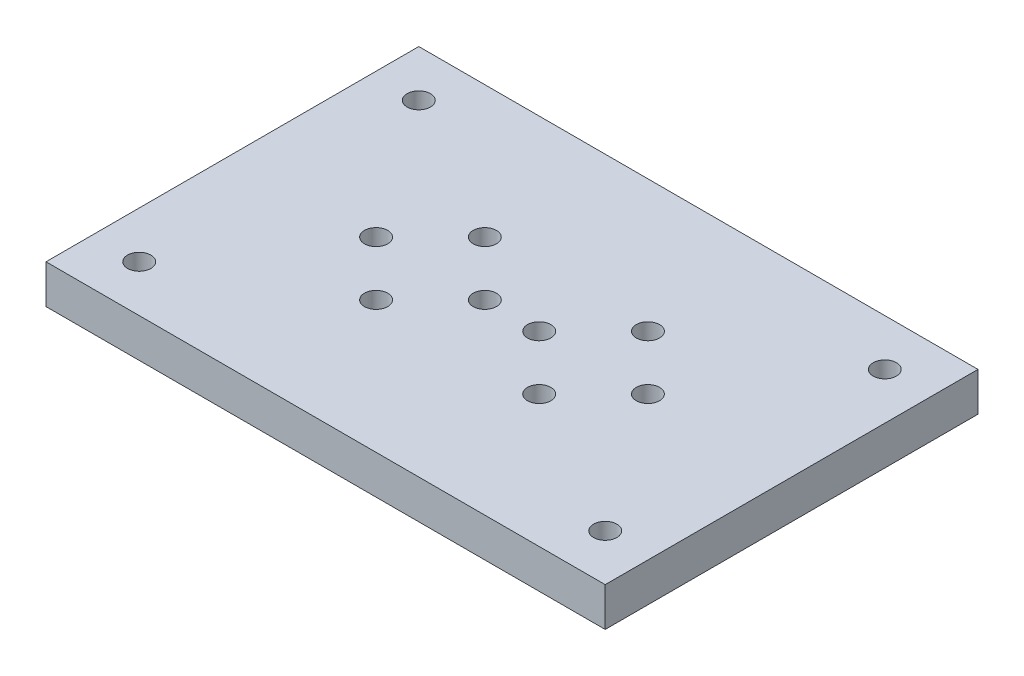
SolidWorks part; units mm, degrees
ref_plane "Front Plane" through (0, 0, 0) normal (0, 0, 1) x (1, 0, 0)
ref_plane "Top Plane" through (0, 0, 0) normal (0, 1, 0) x (1, 0, 0)
ref_plane "Right Plane" through (0, 0, 0) normal (1, 0, 0) x (0, 0, -1)
sketch "Sketch1" plane through (0, 0, 0) normal (0, 1, 0) x (1, 0, 0)
  line L0 (-36, 0) -> (36, 0) construction
  line L1 (-36, -24) -> (36, -24)
  line L2 (-36, -24) -> (-36, 24)
  line L3 (-36, 24) -> (36, 24)
  line L4 (36, -24) -> (36, 24)
  line L5 (-36, -24) -> (36, 24) construction
  line L6 (-36, 24) -> (36, -24) construction
  line L7 (0, -24) -> (0, 24) construction
  line L8 (-30, 18) -> (-30, -18) construction
  circle A0 centre (-17.5, 0) radius 1.5
  circle A1 centre (-10.5, 7) radius 1.5
  circle A2 centre (-3.5, 0) radius 1.5
  circle A3 centre (-10.5, -7) radius 1.5
  circle A4 centre (-30, 18) radius 1.5
  circle A5 centre (-30, -18) radius 1.5
  circle A6 centre (10.5, 7) radius 1.5
  circle A7 centre (3.5, 0) radius 1.5
  circle A8 centre (10.5, -7) radius 1.5
  circle A9 centre (17.5, 0) radius 1.5
  circle A10 centre (30, 18) radius 1.5
  circle A11 centre (30, -18) radius 1.5
  point P0 (0, 0)
  point P12 (-10.5, 0)
  point P22 (-10.5, 0)
  dimension "D1" = 3
  dimension "D3" = 7
  dimension "D7" = 6
  dimension "D8" = 6
  dimension "D9" = 6
  dimension "D2" = 10.5
  dimension "D5" = 72
  dimension "D6" = 48
  dimension "D4" = 4
extrude "Boss-Extrude1" add sketch "Sketch1" along normal blind 5
